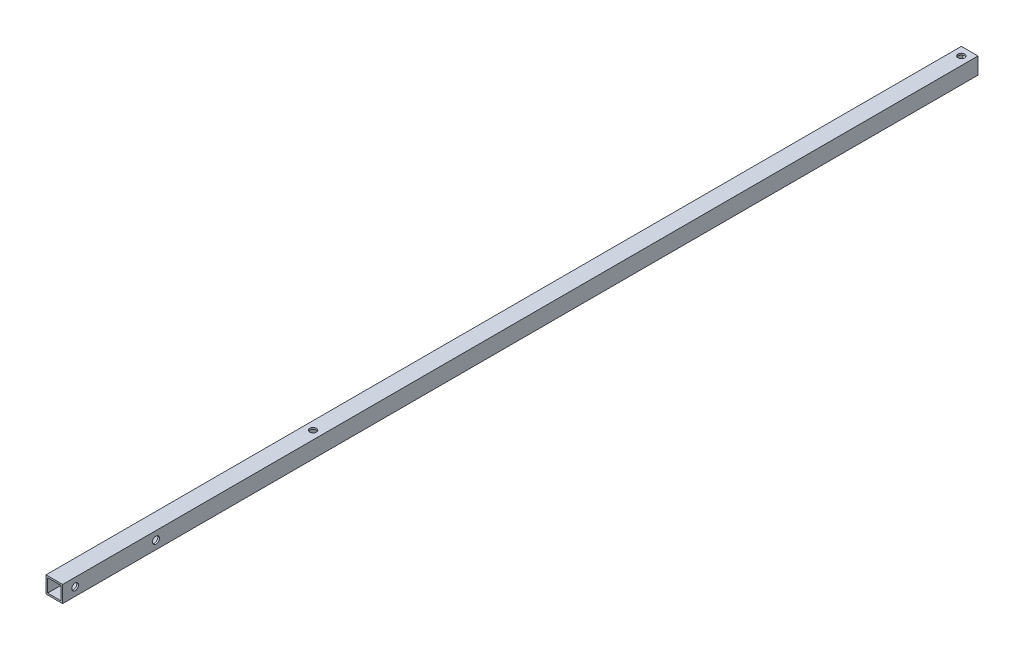
SolidWorks part; units mm, degrees
material "5052-H34"
ref_plane "正面" through (0, 0, 0) normal (0, 0, 1) x (1, 0, 0)
ref_plane "平面" through (0, 0, 0) normal (0, 1, 0) x (1, 0, 0)
ref_plane "右側面" through (0, 0, 0) normal (1, 0, 0) x (0, 0, -1)
sketch "ｽｹｯﾁ1" plane through (0, 0, 0) normal (0, 0, 1) x (1, 0, 0)
  line L1 (-5, -5) -> (5, -5)
  line L2 (-5, -5) -> (-5, 5)
  line L3 (-5, 5) -> (5, 5)
  line L4 (5, -5) -> (5, 5)
  line L5 (-5, -5) -> (5, 5) construction
  line L6 (-5, 5) -> (5, -5) construction
  point P0 (0, 0)
  dimension "D1" = 10
extrude "押し出し-薄板1" add sketch "ｽｹｯﾁ1" along normal blind 550 thin thin type one direction reverse wall 1
sketch "ｽｹｯﾁ2" plane through (0, 5, 0) normal (0, 1, 0) x (1, 0, 0)
  line L0 (0, 0) -> (0, -550) construction
  line L1 (5, -550) -> (-5, -550) construction
  line L2 (5, 0) -> (-5, 0) construction
  circle A0 centre (0, -5) radius 2
  circle A1 centre (0, -394.5) radius 2
  dimension "D1" = 5
  dimension "D2" = 389.5
  dimension "D3" = 4
extrude "ｶｯﾄ - 押し出し1" cut sketch "ｽｹｯﾁ2" against normal through all
sketch "ｽｹｯﾁ3" plane through (5, 0, 0) normal (1, 0, 0) x (0, 0, -1)
  line L0 (0, 0) -> (50000, 0) construction
  line L1 (0, -5) -> (0, 5) construction
  circle A0 centre (-493.91, 0) radius 2.1
  dimension "D1" = 493.91
  dimension "D2" = 4.2
extrude "ｶｯﾄ - 押し出し2" cut sketch "ｽｹｯﾁ3" against normal through all
sketch "ｽｹｯﾁ4" plane through (5, 0, 0) normal (1, 0, 0) x (0, 0, -1)
  line L0 (-550, 0) -> (-542.5, 0) construction
  line L1 (-550, -5) -> (-550, 5) construction
  circle A0 centre (-542.5, 0) radius 2
  dimension "D1" = 4
  dimension "D2" = 7.5
extrude "ｶｯﾄ - 押し出し3" cut sketch "ｽｹｯﾁ4" against normal through all
